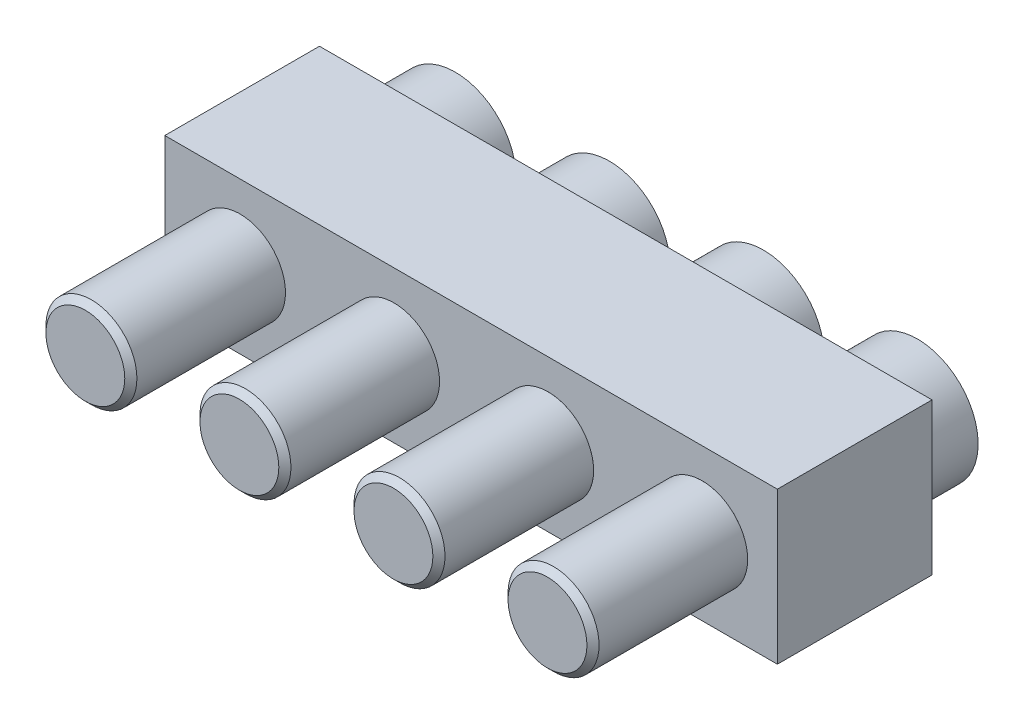
SolidWorks part; units mm, degrees
ref_plane "前视基准面" through (0, 0, 0) normal (0, 0, 1) x (1, 0, 0)
ref_plane "上视基准面" through (0, 0, 0) normal (0, 1, 0) x (1, 0, 0)
ref_plane "右视基准面" through (0, 0, 0) normal (1, 0, 0) x (0, 0, -1)
sketch "草图1" plane through (0, 0, 0) normal (0, 0, 1) x (1, 0, 0)
  line L0 (0, 1.25) -> (10.1, 1.25) construction
  line L1 (0, 0) -> (10.1, 0)
  line L2 (0, 0) -> (0, 2.5)
  line L3 (0, 2.5) -> (10.1, 2.5)
  line L4 (10.1, 0) -> (10.1, 2.5)
  line L5 (5.05, 2.5) -> (5.05, 0) construction
  circle A0 centre (3.78, 1.25) radius 0.75
  circle A2 centre (1.24, 1.25) radius 0.75
  circle A3 centre (8.86, 1.25) radius 0.75
  circle A4 centre (6.32, 1.25) radius 0.75
  dimension "D3" = 1.5
  dimension "D5" = 2
  dimension "D1" = 10.1
  dimension "D2" = 2.5
  dimension "D4" = 1.27
  dimension "D6" = 2.54
extrude "凸台-拉伸1" add sketch "草图1" along normal blind 2.55
ref_plane "基准面1" through (0, 0, 0) normal (0, 0, -1) x (-1, 0, 0)
sketch "草图2" plane through (0, 0, 0) normal (0, 0, -1) x (-1, 0, 0)
  line L0 (-5.05, 2.5) -> (-5.05, 0) construction
  line L1 (-10.1, 2.5) -> (0, 2.5) construction
  line L2 (0, 0) -> (-10.1, 0) construction
  circle A0 centre (-6.32, 1.25) radius 1
  circle A1 centre (-8.86, 1.25) radius 1
  circle A2 centre (-3.78, 1.25) radius 1
  circle A3 centre (-1.24, 1.25) radius 1
  dimension "D1" = 2
extrude "凸台-拉伸2" add sketch "草图2" along normal blind 1
ref_plane "基准面2" through (0, 0, 2.55) normal (0, 0, 1) x (1, 0, 0)
sketch "草图3" plane through (0, 0, 2.55) normal (0, 0, 1) x (1, 0, 0)
  circle A0 centre (3.78, 1.25) radius 0.75
  circle A1 centre (1.24, 1.25) radius 0.75
  circle A2 centre (6.32, 1.25) radius 0.75
  circle A3 centre (8.86, 1.25) radius 0.75
extrude "凸台-拉伸3" add sketch "草图3" along normal blind 2.55 separate body
chamfer "倒角1" distance 0.1 angle 45 1 edges at (9.61, 1.25, 5.1)
chamfer "倒角2" distance 0.1 angle 45 1 edges at (7.07, 1.25, 5.1)
chamfer "倒角3" distance 0.1 angle 45 1 edges at (4.53, 1.25, 5.1)
chamfer "倒角4" distance 0.1 angle 45 1 edges at (1.99, 1.25, 5.1)
